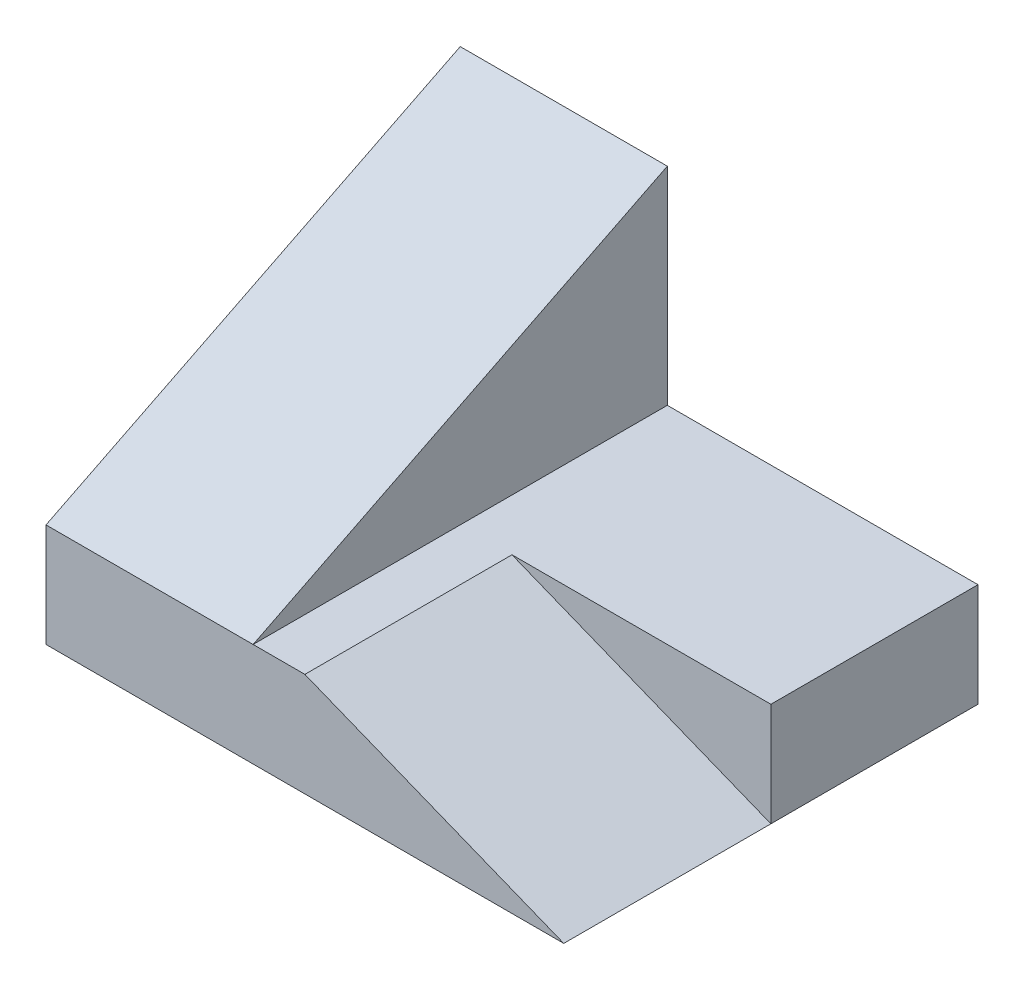
SolidWorks part; units mm, degrees
ref_plane "Front Plane" through (0, 0, 0) normal (0, 0, 1) x (1, 0, 0)
ref_plane "Top Plane" through (0, 0, 0) normal (0, 1, 0) x (1, 0, 0)
ref_plane "Right Plane" through (0, 0, 0) normal (1, 0, 0) x (0, 0, -1)
sketch "Sketch1" plane through (0, 0, 0) normal (0, 1, 0) x (1, 0, 0)
  line L1 (-25, 20) -> (25, 20)
  line L2 (-25, 20) -> (-25, -20)
  line L3 (-25, -20) -> (25, -20)
  line L4 (25, 20) -> (25, -20)
  line L5 (-25, 20) -> (25, -20) construction
  line L6 (-25, -20) -> (25, 20) construction
  point P0 (0, 0)
extrude "Boss-Extrude1" add sketch "Sketch1" along normal blind 10
sketch "Sketch2" plane through (0, 10, 0) normal (0, 1, 0) x (1, 0, 0)
  line L1 (-25, 20) -> (-5, 20)
  line L2 (-25, 20) -> (-25, -20)
  line L3 (-25, -20) -> (-5, -20)
  line L4 (-5, 20) -> (-5, -20)
extrude "Boss-Extrude2" add sketch "Sketch2" along normal blind 20
sketch "Sketch3" plane through (-5, 0, 0) normal (1, 0, 0) x (0, 0, -1)
  line L0 (20, 30) -> (-20, 10)
  line L1 (-20, 10) -> (-20, 30)
  line L2 (-20, 30) -> (20, 30)
extrude "Cut-Extrude1" cut sketch "Sketch3" against normal blind 20
sketch "Sketch5" plane through (0, 0, 20) normal (0, 0, 1) x (1, 0, 0)
  line L0 (0, 10) -> (25, 0)
  line L1 (-5, 10) -> (25, 10) construction
  line L2 (25, 0) -> (25, 10)
  line L3 (25, 10) -> (0, 10)
extrude "Cut-Extrude5" cut sketch "Sketch5" against normal blind 20
